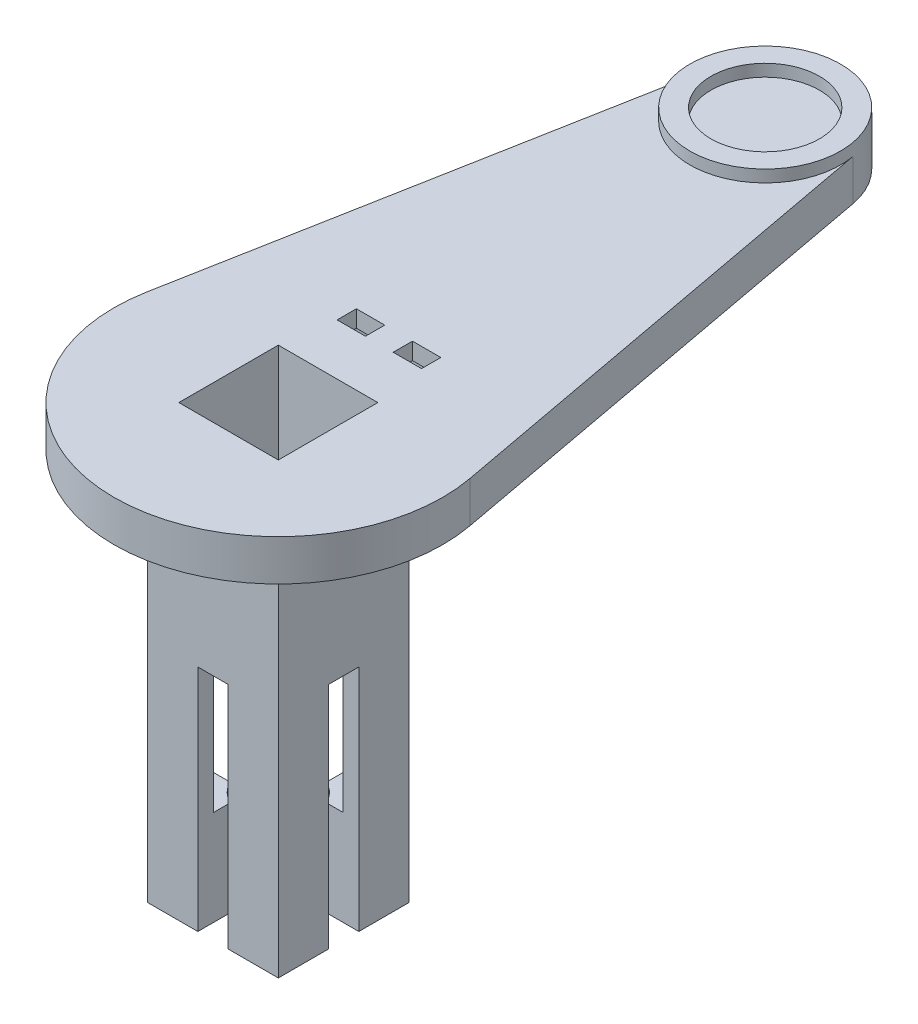
SolidWorks part; units mm, degrees
material "PA Type 6"
ref_plane "Front Plane" through (0, 0, 0) normal (0, 0, 1) x (1, 0, 0)
ref_plane "Top Plane" through (0, 0, 0) normal (0, 1, 0) x (1, 0, 0)
ref_plane "Right Plane" through (0, 0, 0) normal (1, 0, 0) x (0, 0, -1)
sketch "Sketch1" plane through (0, 0, 0) normal (0, 1, 0) x (1, 0, 0)
  line L1 (-12.2897, 83.0333) -> (-26.7915, 4.9776)
  line L2 (12.2897, 83.0333) -> (26.7915, 4.9776)
  arc A0 (-26.7915, 4.9776) -> (26.7915, 4.9776) centre (0, 0) ccw
  arc A1 (12.2897, 83.0333) -> (-12.2897, 83.0333) centre (0, 80.75) ccw
  dimension "D1" = 25
  dimension "D2" = 54.5
extrude "Boss-Extrude1" add sketch "Sketch1" along normal blind 6.8
sketch "Sketch2" plane through (0, 6.8, 0) normal (0, 1, 0) x (1, 0, 0)
  circle A1 centre (0, 80.75) radius 12.5
  circle A2 centre (0, 80.75) radius 9
  dimension "D1" = 3.5
extrude "Boss-Extrude2" add sketch "Sketch2" along normal blind 2
sketch "Sketch3" plane through (0, 6.8, 0) normal (0, 1, 0) x (1, 0, 0)
  line L1 (2.3, 16.75) -> (2.3, 19.95)
  line L2 (7, 19.95) -> (2.3, 19.95)
  line L3 (-7, 16.75) -> (-2.3, 16.75)
  line L4 (-7, 16.75) -> (-7, 19.95)
  line L5 (-7, 19.95) -> (-2.3, 19.95)
  line L6 (-2.3, 16.75) -> (-2.3, 19.95)
  line L11 (7, 16.75) -> (7, 19.95)
  line L12 (7, 16.75) -> (2.3, 16.75)
  point P10 (0, 16.75)
extrude "Cut-Extrude1" cut sketch "Sketch3" against normal blind 10
sketch "Sketch7" plane through (0, 0, 0) normal (0, -1, 0) x (1, 0, 0)
  circle A1 centre (0, 0) radius 21.25
extrude "Cut-Extrude4" cut sketch "Sketch7" against normal blind 4
sketch "Sketch8" plane through (0, 4, 0) normal (0, -1, 0) x (1, 0, 0)
  line L1 (-10.85, -10.85) -> (10.85, -10.85)
  line L2 (-10.85, -10.85) -> (-10.85, 10.85)
  line L3 (-10.85, 10.85) -> (10.85, 10.85)
  line L4 (10.85, -10.85) -> (10.85, 10.85)
  line L5 (-10.85, -10.85) -> (10.85, 10.85) construction
  line L6 (-10.85, 10.85) -> (10.85, -10.85) construction
  point P0 (0, 0)
extrude "Boss-Extrude3" add sketch "Sketch8" along normal blind 69
sketch "Sketch9" plane through (0, 6.8, 0) normal (0, 1, 0) x (1, 0, 0)
  line L1 (-8.25, -8.25) -> (8.25, -8.25)
  line L2 (-8.25, -8.25) -> (-8.25, 8.25)
  line L3 (-8.25, 8.25) -> (8.25, 8.25)
  line L4 (8.25, -8.25) -> (8.25, 8.25)
  line L5 (-8.25, -8.25) -> (8.25, 8.25) construction
  line L6 (-8.25, 8.25) -> (8.25, -8.25) construction
  point P0 (0, 0)
extrude "Cut-Extrude5" cut sketch "Sketch9" against normal blind 56
sketch "Sketch10" plane through (0, -65, 0) normal (0, -1, 0) x (1, 0, 0)
  circle A0 centre (0, 0) radius 6
extrude "Cut-Extrude6" cut sketch "Sketch10" against normal blind 99
sketch "Sketch11" plane through (0, -65, 0) normal (0, -1, 0) x (1, 0, 0)
  line L0 (-6, 2.5) -> (-5.4544, 2.5)
  line L2 (-6, -2.5) -> (-5.4544, -2.5)
  line L4 (-2.5, 6) -> (-2.5, 5.4544)
  line L6 (2.5, 6) -> (2.5, 5.4544)
  line L8 (2.5, 6) -> (2.5, 10.85)
  line L9 (-6, 2.5) -> (-10.85, 2.5)
  line L10 (-2.5, -6) -> (-2.5, -10.85)
  line L11 (6, -2.5) -> (10.85, -2.5)
  line L12 (-2.5, 6) -> (-2.5, 10.85)
  line L13 (-6, -2.5) -> (-10.85, -2.5)
  line L14 (2.5, -6) -> (2.5, -10.85)
  line L15 (6, 2.5) -> (10.85, 2.5)
  line L19 (5.4544, 2.5) -> (6, 2.5)
  line L20 (5.4544, -2.5) -> (6, -2.5)
  line L21 (2.5, -5.4544) -> (2.5, -6)
  line L22 (-2.5, -5.4544) -> (-2.5, -6)
  line L24 (-10.85, 2.5) -> (-10.85, -2.5)
  line L25 (-2.5, 10.85) -> (2.5, 10.85)
  line L26 (10.85, 2.5) -> (10.85, -2.5)
  line L27 (2.5, -10.85) -> (-2.5, -10.85)
  circle A1 centre (0, 0) radius 6 construction
  arc A2 (-5.4544, 2.5) -> (-5.4544, -2.5) centre (0, 0) ccw
  arc A3 (2.5, 5.4544) -> (-2.5, 5.4544) centre (0, 0) ccw
  arc A4 (5.4544, -2.5) -> (5.4544, 2.5) centre (0, 0) ccw
  arc A5 (-2.5, -5.4544) -> (2.5, -5.4544) centre (0, 0) ccw
extrude "Cut-Extrude7" cut sketch "Sketch11" against normal blind 38
